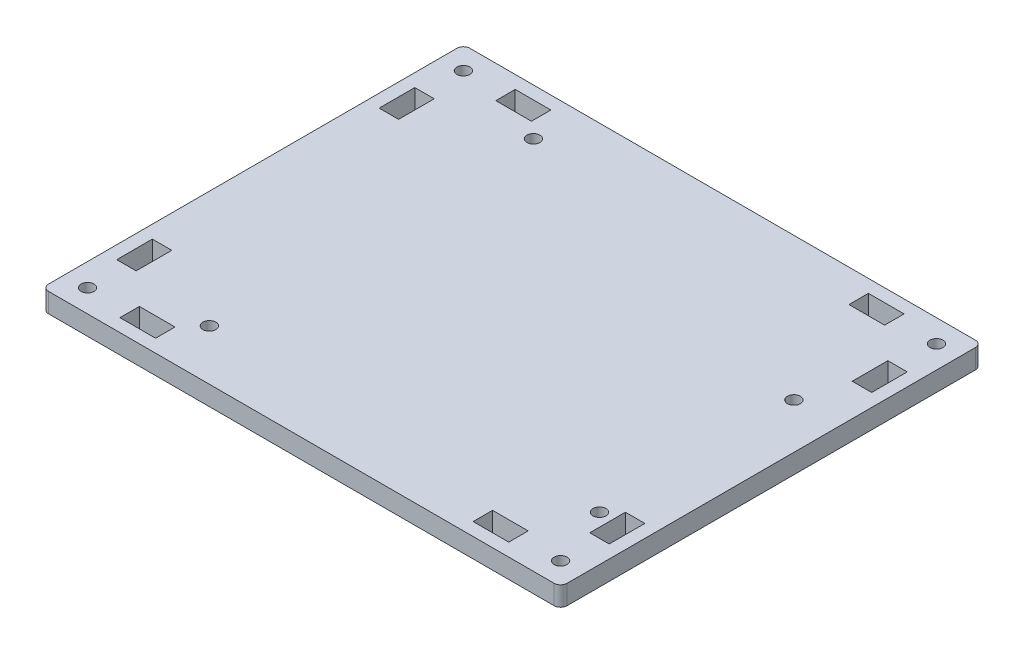
SolidWorks part; units mm, degrees
ref_plane "Alzado" through (0, 0, 0) normal (0, 0, 1) x (1, 0, 0)
ref_plane "Planta" through (0, 0, 0) normal (0, 1, 0) x (1, 0, 0)
ref_plane "Vista lateral" through (0, 0, 0) normal (1, 0, 0) x (0, 0, -1)
sketch "Croquis1" plane through (0, 0, 0) normal (0, 1, 0) x (1, 0, 0)
  line L0 (0, 47.0895) -> (0, -35.8881) construction
  line L1 (-39, -32.5) -> (39, -32.5)
  line L2 (-40, -31.5) -> (-40, 31.5)
  line L3 (-39, 32.5) -> (39, 32.5)
  line L4 (40, -31.5) -> (40, 31.5)
  line L5 (-40, -32.5) -> (40, 32.5) construction
  line L6 (-40, 32.5) -> (40, -32.5) construction
  line L7 (-38, 17.5) -> (-35, 17.5)
  line L8 (-38, 17.5) -> (-38, 23)
  line L9 (-38, 23) -> (-35, 23)
  line L10 (-35, 17.5) -> (-35, 23)
  line L11 (-38, 17.5) -> (-35, 23) construction
  line L12 (-38, 23) -> (-35, 17.5) construction
  line L13 (-38, -23) -> (-35, -23)
  line L14 (-38, -23) -> (-38, -17.5)
  line L15 (-38, -17.5) -> (-35, -17.5)
  line L16 (-35, -23) -> (-35, -17.5)
  line L17 (-38, -23) -> (-35, -17.5) construction
  line L18 (-38, -17.5) -> (-35, -23) construction
  line L19 (30, -27.5) -> (24.5, -30.5) construction
  line L20 (-30, 27.5) -> (-24.5, 27.5)
  line L21 (-30, 27.5) -> (-30, 30.5)
  line L22 (-30, 30.5) -> (-24.5, 30.5)
  line L23 (-24.5, 27.5) -> (-24.5, 30.5)
  line L24 (-30, 27.5) -> (-24.5, 30.5) construction
  line L25 (-30, 30.5) -> (-24.5, 27.5) construction
  line L26 (-30, -30.5) -> (-24.5, -30.5)
  line L27 (-30, -30.5) -> (-30, -27.5)
  line L28 (-30, -27.5) -> (-24.5, -27.5)
  line L29 (-24.5, -30.5) -> (-24.5, -27.5)
  line L30 (-30, -30.5) -> (-24.5, -27.5) construction
  line L31 (-30, -27.5) -> (-24.5, -30.5) construction
  line L32 (30, -30.5) -> (24.5, -27.5) construction
  line L33 (24.5, -30.5) -> (24.5, -27.5)
  line L34 (30, -27.5) -> (24.5, -27.5)
  line L35 (30, -30.5) -> (30, -27.5)
  line L36 (30, -30.5) -> (24.5, -30.5)
  line L37 (38, -17.5) -> (35, -23) construction
  line L38 (38, -23) -> (35, -17.5) construction
  line L39 (35, -23) -> (35, -17.5)
  line L40 (38, -17.5) -> (35, -17.5)
  line L41 (38, -23) -> (38, -17.5)
  line L42 (38, -23) -> (35, -23)
  line L43 (38, 23) -> (35, 17.5) construction
  line L44 (38, 17.5) -> (35, 23) construction
  line L45 (35, 17.5) -> (35, 23)
  line L46 (38, 23) -> (35, 23)
  line L47 (38, 17.5) -> (38, 23)
  line L48 (38, 17.5) -> (35, 17.5)
  line L49 (30, 30.5) -> (24.5, 27.5) construction
  line L50 (30, 27.5) -> (24.5, 30.5) construction
  line L51 (24.5, 27.5) -> (24.5, 30.5)
  line L52 (30, 30.5) -> (24.5, 30.5)
  line L53 (30, 27.5) -> (30, 30.5)
  line L54 (30, 27.5) -> (24.5, 27.5)
  circle A0 centre (-36.5, 29) radius 1
  circle A1 centre (-36.5, -29) radius 1
  circle A2 centre (36.5, -29) radius 1
  circle A3 centre (36.5, 29) radius 1
  circle A4 centre (-22, 25.3) radius 1
  circle A5 centre (-22, -24.7) radius 1
  circle A6 centre (33, 10.5) radius 1
  circle A7 centre (33, -19.5) radius 1
  arc A8 (-39, -32.5) -> (-40, -31.5) centre (-39, -31.5) cw
  arc A9 (39, -32.5) -> (40, -31.5) centre (39, -31.5) ccw
  arc A10 (39, 32.5) -> (40, 31.5) centre (39, 31.5) cw
  arc A11 (-40, 31.5) -> (-39, 32.5) centre (-39, 31.5) cw
  point P0 (0, 0)
  point P8 (-36.5, -20.25)
  point P14 (-36.5, 20.25)
  point P20 (-27.25, 29)
  point P27 (-27.25, -29)
  point P39 (27.25, -29)
  point P46 (36.5, -20.25)
  point P53 (36.5, 20.25)
  point P58 (27.25, 29)
  dimension "D3" = 2
  dimension "D6" = 3.5
  dimension "D7" = 3.5
  dimension "D19" = 2
  dimension "D22" = 7.2
  dimension "D23" = 2
  dimension "D25" = 13
  dimension "D26" = 7
  dimension "D27" = 1
  dimension "D1" = 65
  dimension "D2" = 80
  dimension "D4" = 3.5
  dimension "D5" = 3.5
  dimension "D8" = 35
  dimension "D9" = 9.5
  dimension "D10" = 5.5
  dimension "D11" = 3
  dimension "D12" = 5.5
  dimension "D13" = 3
  dimension "D14" = 5.5
  dimension "D15" = 3
  dimension "D16" = 10
  dimension "D17" = 3
  dimension "D18" = 5.5
  dimension "D20" = 18
  dimension "D21" = 50
  dimension "D24" = 30
extrude "Saliente-Extruir1" add sketch "Croquis1" along normal blind 3
